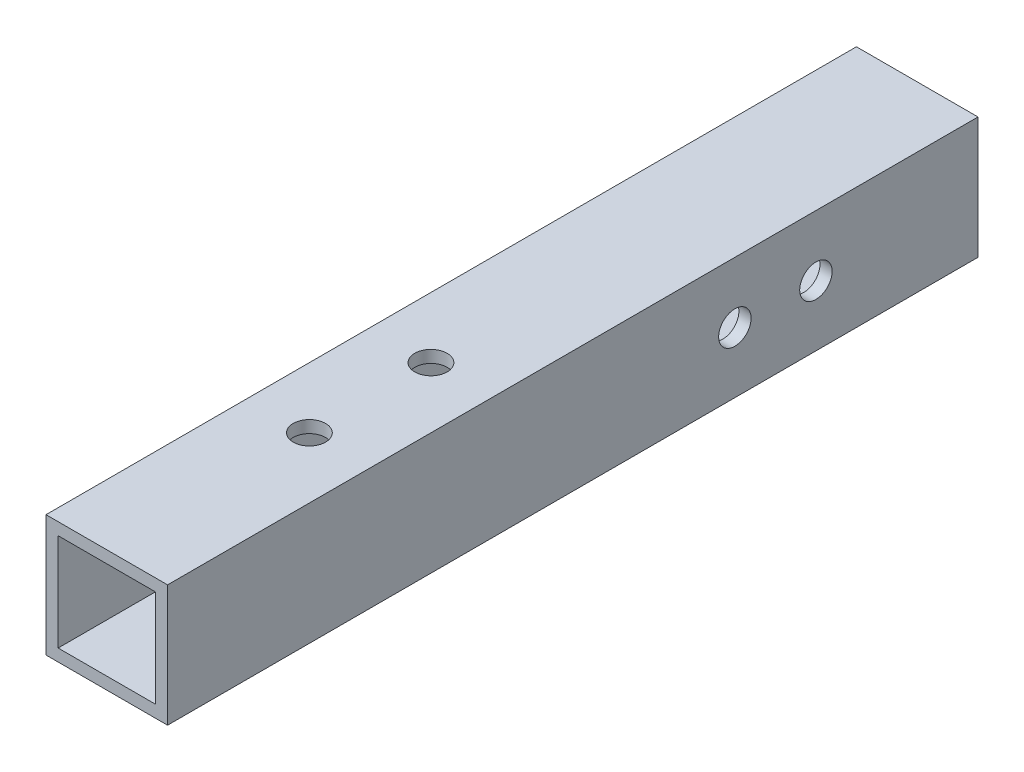
SolidWorks part; units mm, degrees
ref_plane "前视基准面" through (0, 0, 0) normal (0, 0, 1) x (1, 0, 0)
ref_plane "上视基准面" through (0, 0, 0) normal (0, 1, 0) x (1, 0, 0)
ref_plane "右视基准面" through (0, 0, 0) normal (1, 0, 0) x (0, 0, -1)
sketch "草图1" plane through (0, 0, 0) normal (0, 0, 1) x (1, 0, 0)
  line L1 (-6, 6) -> (6, 6)
  line L2 (-6, 6) -> (-6, -6)
  line L3 (-6, -6) -> (6, -6)
  line L4 (6, 6) -> (6, -6)
  line L5 (-6, 6) -> (6, -6) construction
  line L6 (-6, -6) -> (6, 6) construction
  line L7 (-7.5, -7.5) -> (7.5, -7.5)
  line L8 (-7.5, -7.5) -> (-7.5, 7.5)
  line L9 (-7.5, 7.5) -> (7.5, 7.5)
  line L10 (7.5, -7.5) -> (7.5, 7.5)
  line L11 (-7.5, -7.5) -> (7.5, 7.5) construction
  line L12 (-7.5, 7.5) -> (7.5, -7.5) construction
  point P0 (0, 0)
  point P5 (0, 0)
  dimension "D1" = 15
  dimension "D2" = 15
  dimension "D3" = 1.5
  dimension "D4" = 1.5
extrude "凸台-拉伸1" add sketch "草图1" along normal blind 100
sketch "草图4" plane through (0, -7.5, 0) normal (0, -1, 0) x (1, 0, 0)
  line L0 (-7.5, 100) -> (7.5, 100) construction
  circle A0 centre (0, 75) radius 2
  circle A1 centre (0, 60) radius 2
  dimension "D1" = 4
  dimension "D3" = 15
  dimension "D2" = 25
extrude "切除-拉伸2" cut sketch "草图4" against normal blind 75
sketch "草图5" plane through (-7.5, 0, 0) normal (-1, 0, 0) x (0, 0, 1)
  line L0 (0, 7.5) -> (0, -7.5) construction
  line L1 (0, 0) -> (42.1355, 0) construction
  circle A0 centre (20, 0) radius 2
  circle A1 centre (30, 0) radius 2
  dimension "D1" = 4
  dimension "D2" = 4
  dimension "D3" = 10
  dimension "D4" = 20
extrude "切除-拉伸3" cut sketch "草图5" against normal through all
